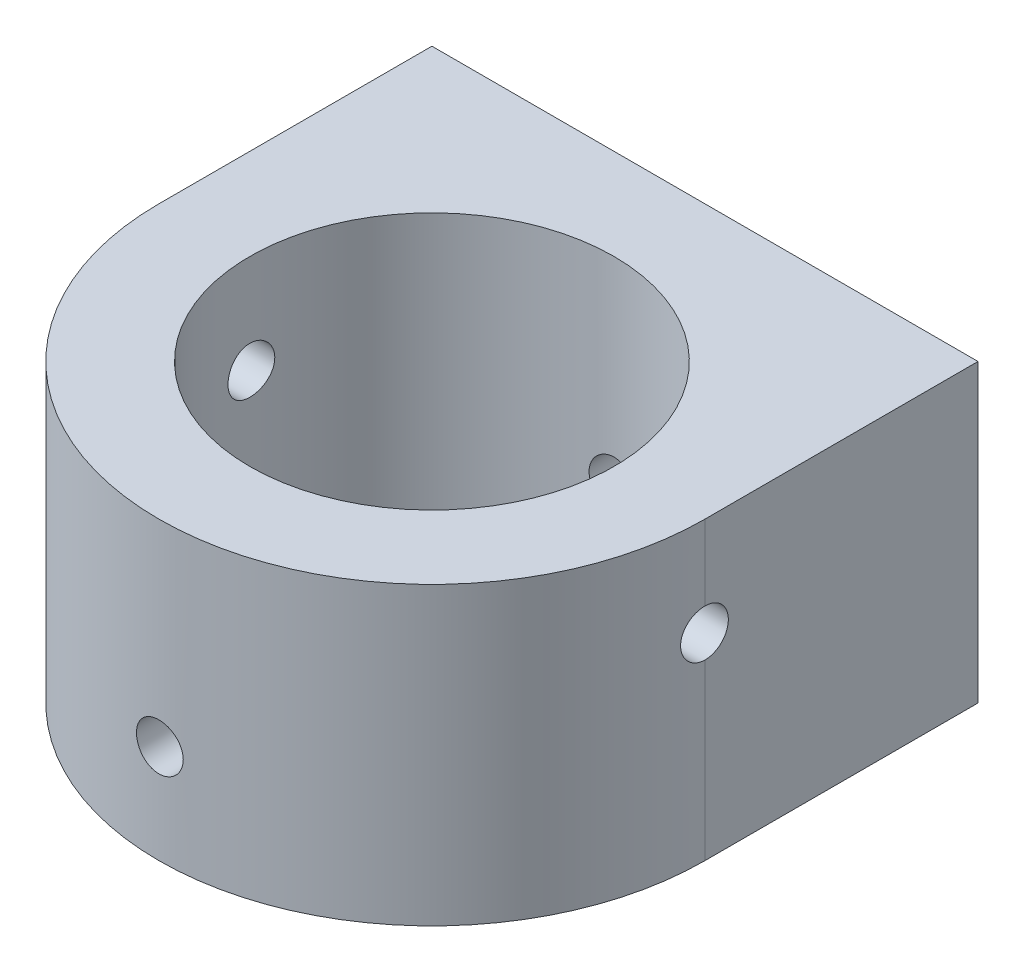
SolidWorks part; units mm, degrees
ref_plane "Front Plane" through (0, 0, 0) normal (1, 0, 0) x (0, 1, 0)
ref_plane "Top Plane" through (0, 0, 0) normal (0, 0, 1) x (0, 1, 0)
ref_plane "Right Plane" through (0, 0, 0) normal (0, 1, 0) x (-1, 0, 0)
sketch "Sketch1" plane through (0, 0, 0) normal (0, 1, 0) x (-1, 0, 0)
  line L0 (-38.1, 0) -> (-38.1, -38.1)
  line L1 (-38.1, -38.1) -> (38.1, -38.1)
  line L2 (38.1, -38.1) -> (38.1, 0)
  circle A0 centre (0, 0) radius 25.4 construction
  circle A1 centre (0, 0) radius 38.1 construction
  arc A2 (-38.1, 0) -> (38.1, 0) centre (0, 0) cw
  dimension "D1" = 50.8
  dimension "D2" = 12.7
extrude "Boss-Extrude1" add sketch "Sketch1" along normal blind 41.275
sketch "Sketch2" plane through (0, 41.275, 0) normal (0, 1, 0) x (-1, 0, 0)
  circle A0 centre (0, 0) radius 25.4 construction
  circle A1 centre (0, 0) radius 25.4
extrude "Cut-Extrude1" cut sketch "Sketch2" against normal through all both and the other way through all
sketch "Sketch3" plane through (0, 0, 0) normal (0, 0, 1) x (0, 1, 0)
  line L0 (0, 0) -> (13.7583, 0) construction
  line L1 (13.7583, 0) -> (27.5167, 0) construction
  line L2 (27.5167, 0) -> (41.275, 0) construction
  line L3 (41.275, -38.1) -> (41.275, 38.1) construction
  circle A0 centre (13.7583, 0) radius 3.2639
  point P0 (13.7583, 0)
  point P1 (27.5167, 0)
  dimension "D1" = 6.5278
extrude "Cut-Extrude2" cut sketch "Sketch3" against normal through all both and the other way through all
sketch "Sketch4" plane through (0, 0, 0) normal (1, 0, 0) x (0, 1, 0)
  circle A0 centre (27.5167, 0) radius 3.2639
  point P0 (27.5167, 0)
  dimension "D1" = 6.5278
extrude "Cut-Extrude3" cut sketch "Sketch4" against normal through all both and the other way through all
